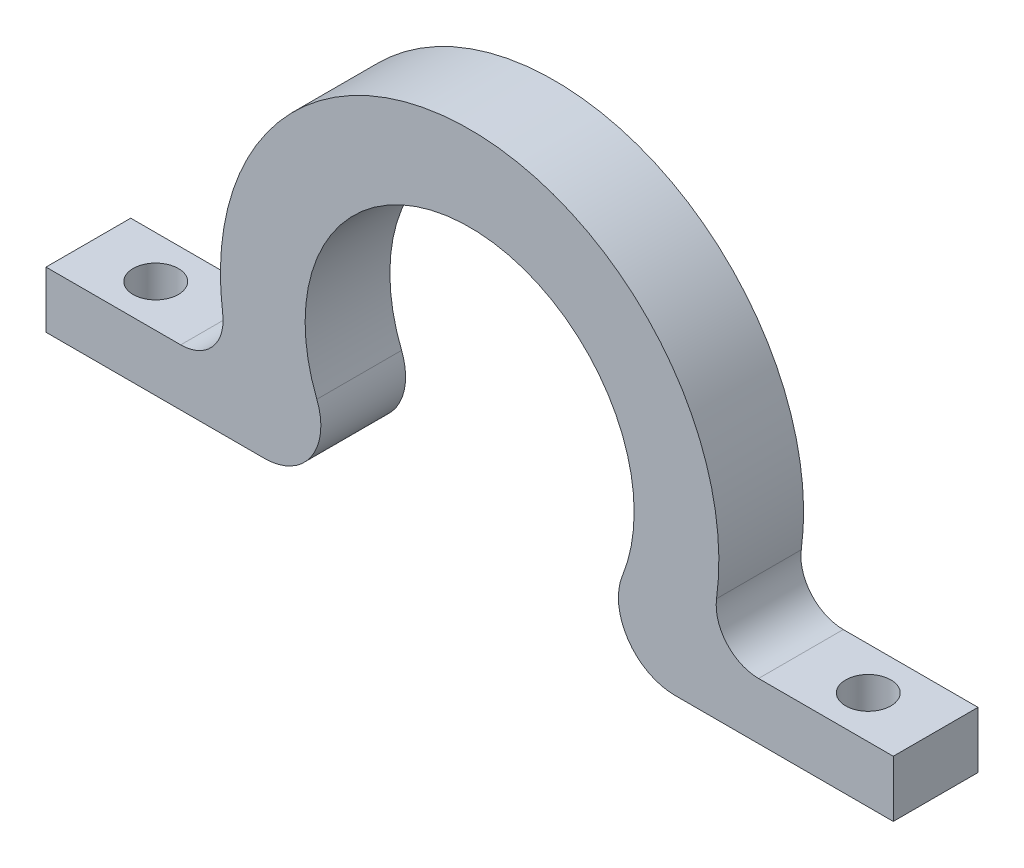
SolidWorks part; units mm, degrees
material "Oak"
ref_plane "Front Plane" through (0, 0, 0) normal (0, 0, 1) x (1, 0, 0)
ref_plane "Top Plane" through (0, 0, 0) normal (0, 1, 0) x (1, 0, 0)
ref_plane "Right Plane" through (0, 0, 0) normal (1, 0, 0) x (0, 0, -1)
sketch "Sketch1" plane through (0, 0, 0) normal (0, 0, 1) x (1, 0, 0)
  line L0 (-14.5356, -9.8) -> (-30, -9.8)
  line L5 (-30, -9.8) -> (-30, -5.8)
  line L6 (-30, -5.8) -> (-20.4593, -5.8)
  line L7 (0, -55) -> (0, 55) construction
  line L8 (30, -5.8) -> (20.4593, -5.8)
  line L9 (30, -9.8) -> (30, -5.8)
  line L10 (14.5356, -9.8) -> (30, -9.8)
  arc A0 (10.8204, -4.3176) -> (-10.8204, -4.3176) centre (0, 0) ccw
  arc A1 (17.487, -2.3932) -> (-17.487, -2.3932) centre (0, 0) ccw
  arc A2 (-17.487, -2.3932) -> (-20.4593, -5.8) centre (-20.4593, -2.8) cw
  arc A3 (17.487, -2.3932) -> (20.4593, -5.8) centre (20.4593, -2.8) ccw
  circle A4 centre (0, 0) radius 17.65 construction
  circle A5 centre (0, 0) radius 11.65 construction
  arc A6 (14.5356, -9.8) -> (10.8204, -4.3176) centre (14.5356, -5.8) cw
  arc A7 (-14.5356, -9.8) -> (-10.8204, -4.3176) centre (-14.5356, -5.8) ccw
  point P1 (0, 0)
  point P8 (-32.2554, -9.8)
  point P9 (-6.2994, -9.8)
  point P25 (6.2994, -9.8)
  point P28 (-6.2994, -9.8)
  dimension "D1" = 23.3
  dimension "D6" = 3
  dimension "D7" = 4
  dimension "D2" = 9.8
  dimension "D4" = 30
  dimension "D5" = 4
  dimension "D3" = 6
extrude "Boss-Extrude1" add sketch "Sketch1" along normal blind 6
sketch "Sketch2" plane through (0, -5.8, 0) normal (0, 1, 0) x (1, 0, 0)
  line L0 (-30, -6) -> (-30, 0) construction
  line L1 (-20.4593, 0) -> (-30, 0) construction
  line L2 (0, -3.3) -> (0, 3.3) construction
  circle A0 centre (-25.2296, -3) radius 1.6
  circle A1 centre (25.2296, -3) radius 1.6
  point P4 (-30, -3)
  point P7 (-25.2296, 0)
  dimension "D1" = 3.2
extrude "Cut-Extrude1" cut sketch "Sketch2" against normal through all
